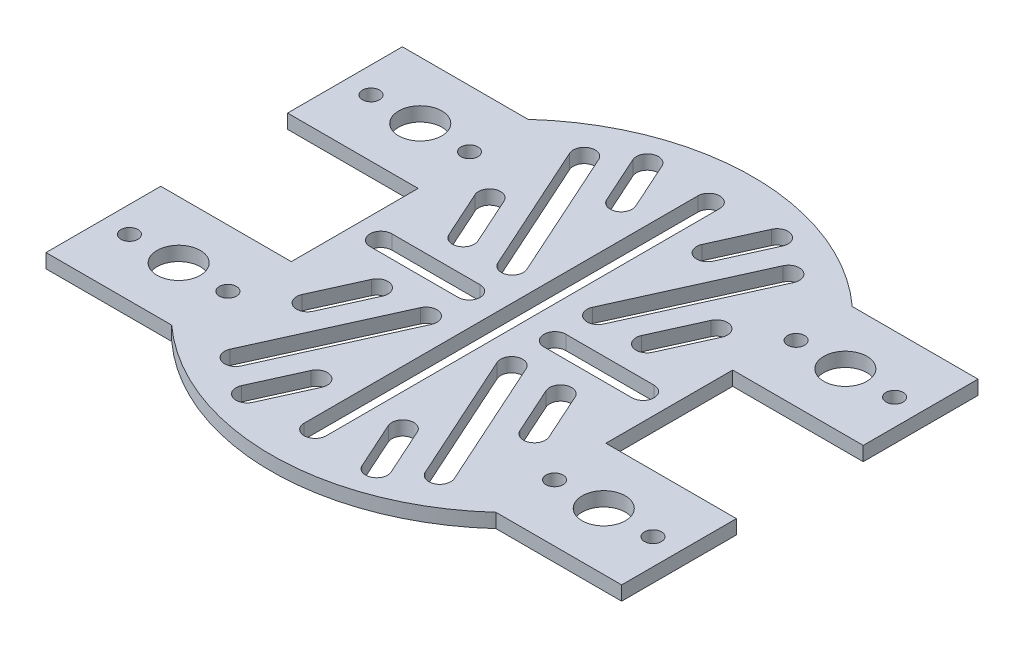
SolidWorks part; units mm, degrees
ref_plane "Front Plane" through (0, 0, 0) normal (0, 0, 1) x (1, 0, 0)
ref_plane "Top Plane" through (0, 0, 0) normal (0, 1, 0) x (1, 0, 0)
ref_plane "Right Plane" through (0, 0, 0) normal (1, 0, 0) x (0, 0, -1)
sketch "Sketch1" plane through (0, 0, 0) normal (0, 1, 0) x (1, 0, 0)
  line L0 (22.2, 8.95) -> (22.2, -8.95)
  line L1 (-40.625, 25.15) -> (-22.8796, 25.15)
  line L2 (-40.625, 25.15) -> (-40.625, 8.95)
  line L3 (-40.625, 8.95) -> (-22.2, 8.95)
  line L4 (40.625, 25.15) -> (40.625, 8.95)
  line L5 (40.625, -8.95) -> (22.2, -8.95)
  line L6 (40.625, -8.95) -> (40.625, -25.15)
  line L7 (40.625, -25.15) -> (22.8796, -25.15)
  line L8 (-40.625, -8.95) -> (-40.625, -25.15)
  line L10 (-22.2, 8.95) -> (-22.2, -8.95)
  line L13 (22.8796, 25.15) -> (40.625, 25.15)
  line L14 (22.2, 8.95) -> (40.625, 8.95)
  line L15 (-55, 0) -> (55, 0) construction
  line L16 (-22.8796, -25.15) -> (-40.625, -25.15)
  line L17 (-22.2, -8.95) -> (-40.625, -8.95)
  arc A0 (-22.8796, -25.15) -> (22.8796, -25.15) centre (0, 0) ccw
  arc A1 (22.8796, 25.15) -> (-22.8796, 25.15) centre (0, 0) ccw
  point P16 (-22.2, 0)
  dimension "D1" = 34
  dimension "D2" = 16.2
  dimension "D3" = 17.9
  dimension "D4" = 81.25
  dimension "D5" = 44.4
extrude "Boss-Extrude1" add sketch "Sketch1" along normal mid plane 2
sketch "Sketch3" plane through (0, 1, 0) normal (0, 1, 0) x (1, 0, 0)
  line L0 (0, 27.775) -> (0, -27.775) construction
  line L1 (0, -1.1) -> (0, 1.1) construction
  line L2 (1.55, 27.775) -> (1.55, -27.775)
  line L3 (-1.55, 27.775) -> (-1.55, -27.775)
  line L4 (-18.5, 0) -> (-6.05, 0) construction
  line L5 (-1.1, 0) -> (1.1, 0) construction
  line L6 (-18.5, 1.55) -> (-6.05, 1.55)
  line L7 (-18.5, -1.55) -> (-6.05, -1.55)
  line L8 (6.05, 0) -> (18.5, 0) construction
  line L9 (6.05, 1.55) -> (18.5, 1.55)
  line L10 (6.05, -1.55) -> (18.5, -1.55)
  line L11 (6.05, 6.1) -> (14.407, 24.6) construction
  line L20 (-6.05, 0) -> (6.05, 0) construction
  line L21 (4.6374, 6.7381) -> (12.9945, 25.2381)
  line L24 (7.4626, 5.4619) -> (15.8196, 23.9619)
  line L27 (6.1, 21.514) -> (9.1464, 28.2578) construction
  line L28 (4.6874, 22.1521) -> (7.7338, 28.8959)
  line L29 (7.5126, 20.8759) -> (10.559, 27.6197)
  line L30 (12.963, 6.1) -> (16.0094, 12.8438) construction
  line L31 (11.5504, 6.7381) -> (14.5968, 13.4819)
  line L32 (14.3755, 5.4619) -> (17.4219, 12.2057)
  line L33 (-6.05, 6.1) -> (-14.407, 24.6) construction
  line L34 (-4.6374, 6.7381) -> (-12.9945, 25.2381)
  line L35 (-7.4626, 5.4619) -> (-15.8196, 23.9619)
  line L36 (-6.1, 21.514) -> (-9.1464, 28.2578) construction
  line L37 (-4.6874, 22.1521) -> (-7.7338, 28.8959)
  line L38 (-7.5126, 20.8759) -> (-10.559, 27.6197)
  line L39 (-12.963, 6.1) -> (-16.0094, 12.8438) construction
  line L40 (-11.5504, 6.7381) -> (-14.5968, 13.4819)
  line L41 (-14.3755, 5.4619) -> (-17.4219, 12.2057)
  line L42 (-6.05, -6.1) -> (-14.407, -24.6) construction
  line L43 (-4.6374, -6.7381) -> (-12.9945, -25.2381)
  line L44 (-7.4626, -5.4619) -> (-15.8196, -23.9619)
  line L45 (-6.1, -21.514) -> (-9.1464, -28.2578) construction
  line L46 (-4.6874, -22.1521) -> (-7.7338, -28.8959)
  line L47 (-7.5126, -20.8759) -> (-10.559, -27.6197)
  line L48 (-12.963, -6.1) -> (-16.0094, -12.8438) construction
  line L49 (-11.5504, -6.7381) -> (-14.5968, -13.4819)
  line L50 (-14.3755, -5.4619) -> (-17.4219, -12.2057)
  line L51 (6.05, -6.1) -> (14.407, -24.6) construction
  line L52 (4.6374, -6.7381) -> (12.9945, -25.2381)
  line L53 (7.4626, -5.4619) -> (15.8196, -23.9619)
  line L54 (6.1, -21.514) -> (9.1464, -28.2578) construction
  line L55 (4.6874, -22.1521) -> (7.7338, -28.8959)
  line L56 (7.5126, -20.8759) -> (10.559, -27.6197)
  line L57 (12.963, -6.1) -> (16.0094, -12.8438) construction
  line L58 (11.5504, -6.7381) -> (14.5968, -13.4819)
  line L59 (14.3755, -5.4619) -> (17.4219, -12.2057)
  line L60 (40.625, 8.95) -> (40.625, 25.15) construction
  arc A0 (1.55, 27.775) -> (-1.55, 27.775) centre (0, 27.775) ccw
  arc A1 (-1.55, -27.775) -> (1.55, -27.775) centre (0, -27.775) ccw
  arc A2 (-18.5, 1.55) -> (-18.5, -1.55) centre (-18.5, 0) ccw
  arc A3 (-6.05, -1.55) -> (-6.05, 1.55) centre (-6.05, 0) ccw
  arc A4 (6.05, 1.55) -> (6.05, -1.55) centre (6.05, 0) ccw
  arc A5 (18.5, -1.55) -> (18.5, 1.55) centre (18.5, 0) ccw
  arc A18 (4.6374, 6.7381) -> (7.4626, 5.4619) centre (6.05, 6.1) ccw
  arc A19 (15.8196, 23.9619) -> (12.9945, 25.2381) centre (14.407, 24.6) ccw
  arc A20 (4.6874, 22.1521) -> (7.5126, 20.8759) centre (6.1, 21.514) ccw
  arc A21 (10.559, 27.6197) -> (7.7338, 28.8959) centre (9.1464, 28.2578) ccw
  arc A22 (11.5504, 6.7381) -> (14.3755, 5.4619) centre (12.963, 6.1) ccw
  arc A23 (17.4219, 12.2057) -> (14.5968, 13.4819) centre (16.0094, 12.8438) ccw
  arc A24 (-4.6374, 6.7381) -> (-7.4626, 5.4619) centre (-6.05, 6.1) cw
  arc A25 (-15.8196, 23.9619) -> (-12.9945, 25.2381) centre (-14.407, 24.6) cw
  arc A26 (-4.6874, 22.1521) -> (-7.5126, 20.8759) centre (-6.1, 21.514) cw
  arc A27 (-10.559, 27.6197) -> (-7.7338, 28.8959) centre (-9.1464, 28.2578) cw
  arc A28 (-11.5504, 6.7381) -> (-14.3755, 5.4619) centre (-12.963, 6.1) cw
  arc A29 (-17.4219, 12.2057) -> (-14.5968, 13.4819) centre (-16.0094, 12.8438) cw
  arc A30 (-4.6374, -6.7381) -> (-7.4626, -5.4619) centre (-6.05, -6.1) ccw
  arc A31 (-15.8196, -23.9619) -> (-12.9945, -25.2381) centre (-14.407, -24.6) ccw
  arc A32 (-4.6874, -22.1521) -> (-7.5126, -20.8759) centre (-6.1, -21.514) ccw
  arc A33 (-10.559, -27.6197) -> (-7.7338, -28.8959) centre (-9.1464, -28.2578) ccw
  arc A34 (-11.5504, -6.7381) -> (-14.3755, -5.4619) centre (-12.963, -6.1) ccw
  arc A35 (-17.4219, -12.2057) -> (-14.5968, -13.4819) centre (-16.0094, -12.8438) ccw
  arc A36 (4.6374, -6.7381) -> (7.4626, -5.4619) centre (6.05, -6.1) cw
  arc A37 (15.8196, -23.9619) -> (12.9945, -25.2381) centre (14.407, -24.6) cw
  arc A38 (4.6874, -22.1521) -> (7.5126, -20.8759) centre (6.1, -21.514) cw
  arc A39 (10.559, -27.6197) -> (7.7338, -28.8959) centre (9.1464, -28.2578) cw
  arc A40 (11.5504, -6.7381) -> (14.3755, -5.4619) centre (12.963, -6.1) cw
  arc A41 (17.4219, -12.2057) -> (14.5968, -13.4819) centre (16.0094, -12.8438) cw
  circle A42 centre (-36.95, 17.05) radius 1.2
  circle A43 centre (-30, 17.05) radius 3.05
  circle A44 centre (-23.05, 17.05) radius 1.2
  circle A45 centre (23.05, 17.05) radius 1.2
  circle A46 centre (30, 17.05) radius 3.05
  circle A47 centre (36.95, 17.05) radius 1.2
  circle A48 centre (36.95, -17.05) radius 1.2
  circle A49 centre (30, -17.05) radius 3.05
  circle A50 centre (23.05, -17.05) radius 1.2
  circle A51 centre (-23.05, -17.05) radius 1.2
  circle A52 centre (-30, -17.05) radius 3.05
  circle A53 centre (-36.95, -17.05) radius 1.2
  point P5 (0, 0)
  point P10 (-12.275, 0)
  point P19 (12.275, 0)
  point P28 (10.2285, 15.35)
  point P33 (7.6232, 24.8859)
  point P45 (14.4862, 9.4719)
  point P51 (0, 0)
  point P61 (-10.2285, 15.35)
  point P68 (-7.6232, 24.8859)
  point P75 (-14.4862, 9.4719)
  point P82 (-10.2285, -15.35)
  point P89 (-7.6232, -24.8859)
  point P96 (-14.4862, -9.4719)
  point P103 (10.2285, -15.35)
  point P110 (7.6232, -24.8859)
  point P117 (14.4862, -9.4719)
  point P124 (40.625, 17.05)
  dimension "D13" = 2.4
  dimension "D14" = 6.1
  dimension "D1" = 3.1
  dimension "D2" = 55.55
  dimension "D3" = 12.45
  dimension "D4" = 12.1
  dimension "D5" = 20.3
  dimension "D6" = 4.55
  dimension "D7" = 4.55
  dimension "D8" = 3.2
  dimension "D9" = 7.4
  dimension "D10" = 3.2
  dimension "D11" = 4.55
  dimension "D12" = 26.15
  dimension "D15" = 6.95
  dimension "D16" = 6.95
  dimension "D17" = 30
extrude "Cut-Extrude1" cut sketch "Sketch3" against normal through all
